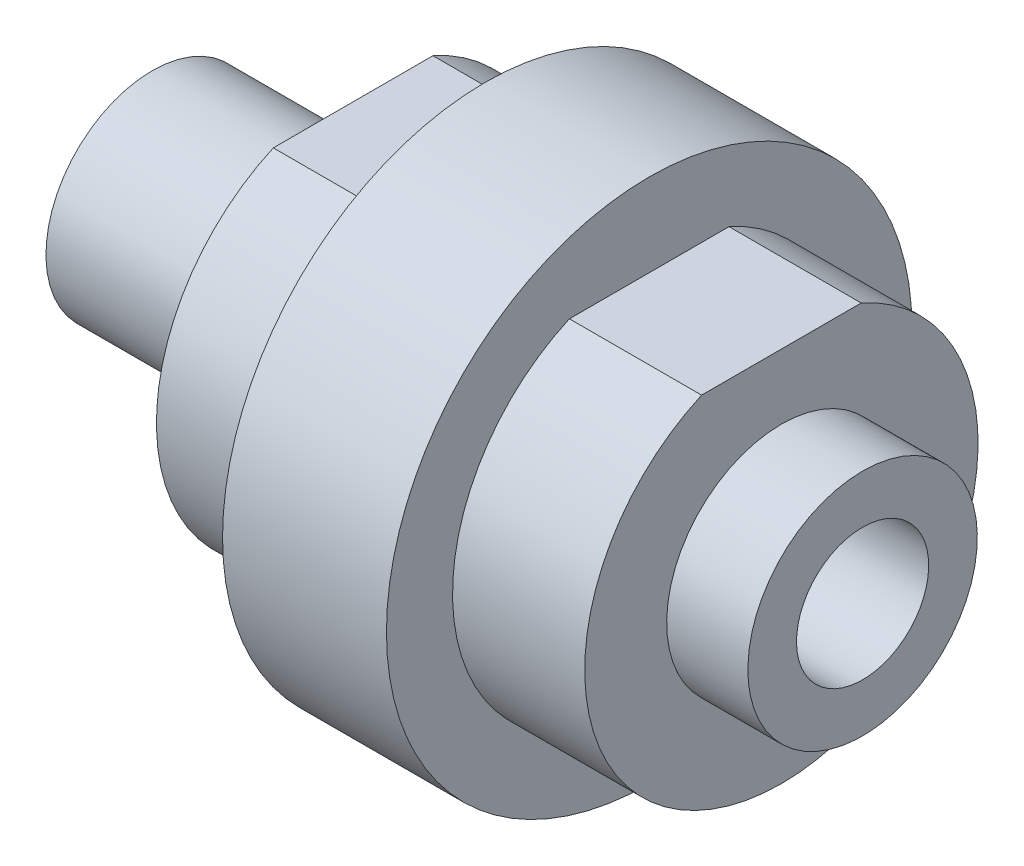
SolidWorks part; units mm, degrees
ref_plane "Front Plane" through (0, 0, 0) normal (0, 0, 1) x (1, 0, 0)
ref_plane "Top Plane" through (0, 0, 0) normal (0, 1, 0) x (1, 0, 0)
ref_plane "Right Plane" through (0, 0, 0) normal (1, 0, 0) x (0, 0, -1)
sketch "Sketch1" plane through (0, 0, 0) normal (0, 0, 1) x (1, 0, 0)
  line L0 (0, 0) -> (0, 5.1054)
  line L1 (0, 5.1054) -> (9.652, 5.1054)
  line L2 (9.652, 5.1054) -> (9.652, 9.4488)
  line L3 (9.652, 9.4488) -> (16.002, 9.4488)
  line L4 (16.002, 9.4488) -> (16.002, 12.6238)
  line L5 (16.002, 12.6238) -> (23.876, 12.6238)
  line L6 (23.876, 12.6238) -> (23.876, 9.4488)
  line L7 (23.876, 9.4488) -> (30.226, 9.4488)
  line L8 (30.226, 9.4488) -> (30.226, 5.5118)
  line L9 (30.226, 5.5118) -> (34.1274, 5.5118)
  line L10 (34.1274, 5.5118) -> (34.1274, 0)
  line L11 (34.1274, 0) -> (0, 0)
  line L12 (34.1274, 3.175) -> (0, 3.175)
  line L13 (34.1274, 0) -> (34.1274, 3.175)
  dimension "D1" = 9.652
  dimension "D2" = 6.35
  dimension "D3" = 7.874
  dimension "D4" = 6.35
  dimension "D5" = 3.9014
  dimension "D6" = 3.937
  dimension "D7" = 3.175
  dimension "D8" = 3.175
  dimension "D9" = 5.1054
  dimension "D11" = 3.175
  dimension "D12" = 5.5118
revolve "Revolve1" add sketch "Sketch1" angle 360 about L11
sketch "Sketch2" plane through (0, 0, 0) normal (0, 0, 1) x (1, 0, 0)
  line L4 (16.002, 9.4488) -> (9.652, 9.4488)
  line L5 (23.876, 9.4488) -> (23.876, 8.636)
  line L6 (23.876, 8.636) -> (30.226, 8.636)
  line L7 (30.226, 8.636) -> (30.226, 9.4488)
  line L8 (30.226, 9.4488) -> (23.876, 9.4488)
  line L9 (9.652, 9.4488) -> (9.652, 8.636)
  line L10 (9.652, 9.4488) -> (9.652, -9.4488) construction
  line L11 (9.652, 8.636) -> (16.002, 8.636)
  line L12 (16.002, 9.4488) -> (16.002, -9.4488) construction
  line L13 (16.002, 8.636) -> (16.002, 9.4488)
  point P14 (30.226, 9.4488)
  dimension "D1" = 0.8128
  dimension "D2" = 6.35
extrude "Cut-Extrude1" cut sketch "Sketch2" against normal through all both and the other way through all
